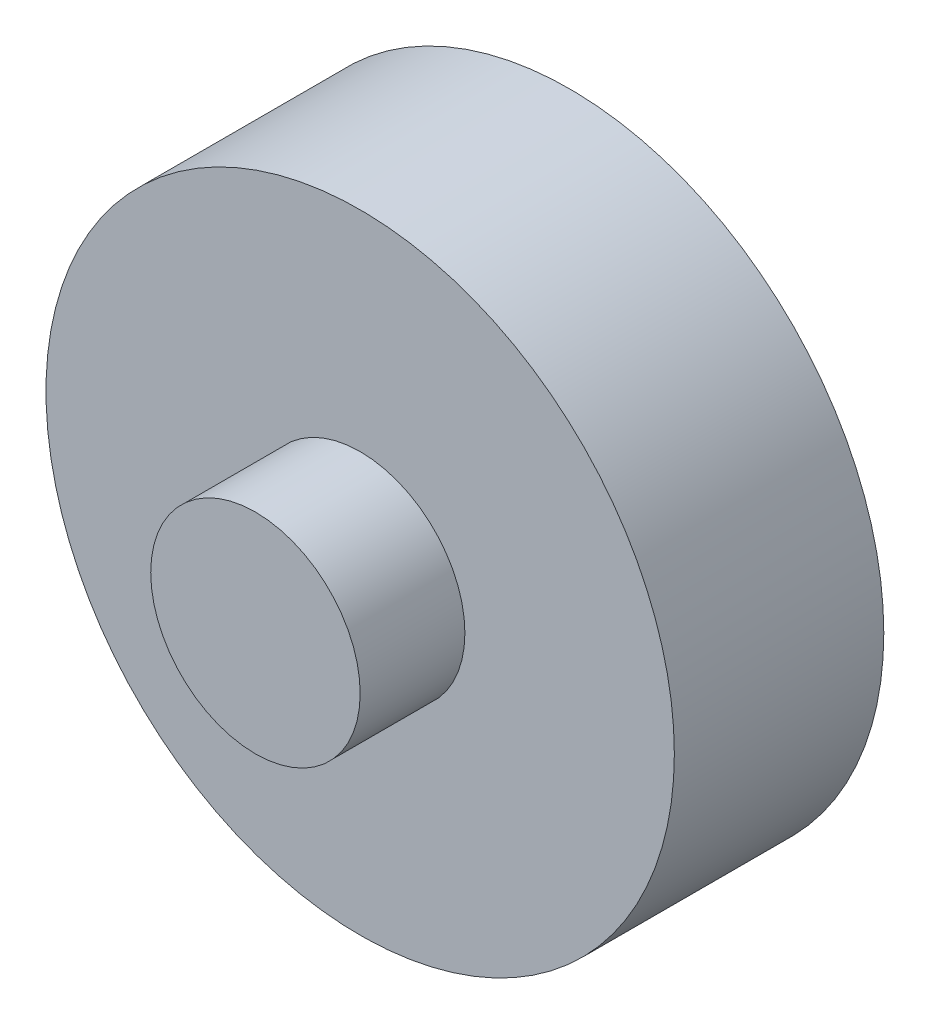
SolidWorks part; units mm, degrees
ref_plane "Front Plane" through (0, 0, 0) normal (0, 0, 1) x (1, 0, 0)
ref_plane "Top Plane" through (0, 0, 0) normal (0, 1, 0) x (1, 0, 0)
ref_plane "Right Plane" through (0, 0, 0) normal (1, 0, 0) x (0, 0, -1)
sketch "Sketch2" plane through (0, 0, 0) normal (0, 0, 1) x (1, 0, 0)
  circle A0 centre (0, 0) radius 7.5
  dimension "D1" = 15
extrude "Boss-Extrude1" add sketch "Sketch2" along normal mid plane 5
sketch "Sketch3" plane through (0, 0, 0) normal (0, 0, 1) x (1, 0, 0)
  circle A0 centre (0, 0) radius 2.5
  dimension "D1" = 5
extrude "Boss-Extrude2" add sketch "Sketch3" along normal blind 5 and the other way blind 5
